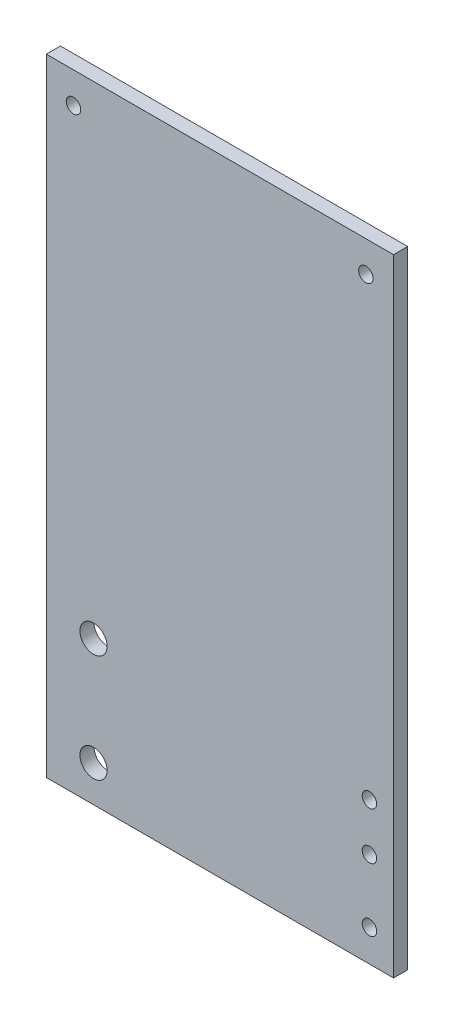
SolidWorks part; units mm, degrees
ref_plane "Front Plane" through (0, 0, 0) normal (0, 0, 1) x (1, 0, 0)
ref_plane "Top Plane" through (0, 0, 0) normal (0, 1, 0) x (1, 0, 0)
ref_plane "Right Plane" through (0, 0, 0) normal (1, 0, 0) x (0, 0, -1)
ref_plane "Dielectric_Layer Layer 1" through (0, 0, 0.79) normal (0, 0, 1) x (1, 0, 0)
sketch "Sketch1" plane through (0, 0, 0) normal (0, 0, 1) x (1, 0, 0)
  line L0 (0, 0) -> (0, 35.05)
  line L1 (0, 35.05) -> (19.43, 35.05)
  line L2 (19.43, 35.05) -> (19.43, 0)
  line L3 (19.43, 0) -> (0, 0)
extrude "Board_Outline" add sketch "Sketch1" along normal blind 0.79 separate body
sketch "Sketch2" plane through (0, 0, 0) normal (0, 0, 1) x (1, 0, 0)
  circle A0 centre (18.08, 5.31) radius 0.405
  circle A1 centre (17.88, 33.32) radius 0.405
  circle A2 centre (2.64, 8.05) radius 0.76
  circle A3 centre (2.64, 2.03) radius 0.76
  circle A4 centre (18.08, 7.96) radius 0.405
  circle A5 centre (1.52, 33.32) radius 0.405
  circle A6 centre (18.08, 1.78) radius 0.405
extrude "PTH" cut sketch "Sketch2" along normal through all
